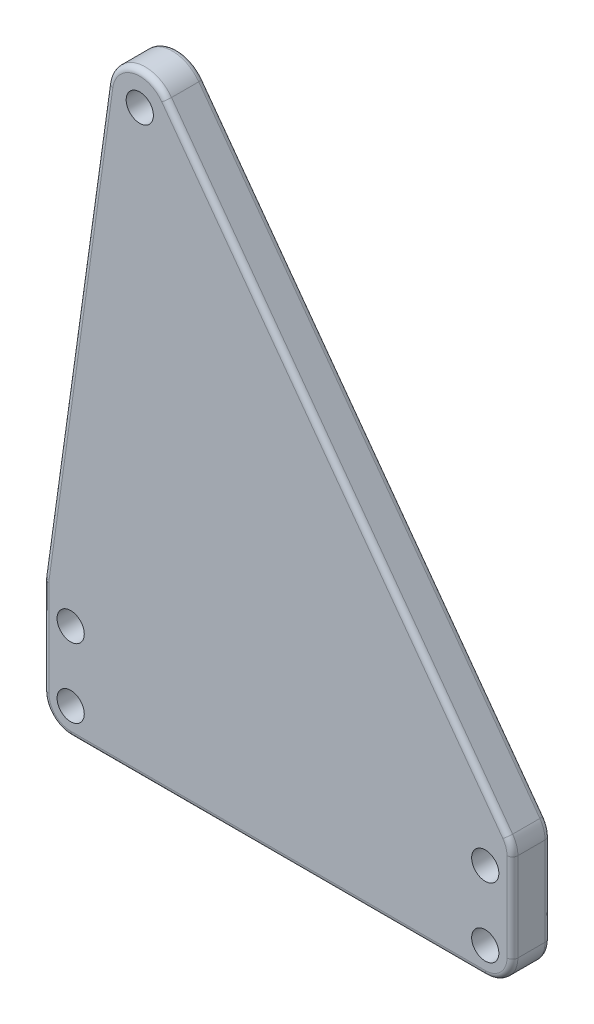
SolidWorks part; units mm, degrees
ref_plane "Front Plane" through (0, 0, 0) normal (0, 0, 1) x (1, 0, 0)
ref_plane "Top Plane" through (0, 0, 0) normal (0, 1, 0) x (1, 0, 0)
ref_plane "Right Plane" through (0, 0, 0) normal (1, 0, 0) x (0, 0, -1)
sketch "Sketch1" plane through (0, 0, 0) normal (0, 0, 1) x (1, 0, 0)
  line L2 (-17.7, -83.6918) -> (-17.7, -106.6)
  line L3 (-17.7, -106.6) -> (68.5, -106.6)
  line L4 (68.5, -83.6918) -> (68.5, -106.6)
  line L6 (-17.7, -83.6918) -> (-5.9428, 0.8267)
  line L7 (68.5, -83.6918) -> (4.8467, 3.5368)
  circle A0 centre (0, 0) radius 2.5
  circle A1 centre (-12.7, -88.9) radius 2.5
  circle A2 centre (-12.7, -101.6) radius 2.5
  circle A3 centre (63.5, -88.9) radius 2.5
  circle A4 centre (63.5, -101.6) radius 2.5
  circle A6 centre (0, 0) radius 6
  dimension "D1" = 5
  dimension "D9" = 12
  dimension "D2" = 101.6
  dimension "D3" = 12.7
  dimension "D4" = 12.7
  dimension "D5" = 76.2
  dimension "D6" = 5
  dimension "D7" = 5
  dimension "D8" = 5
extrude "Boss-Extrude1" add sketch "Sketch1" along normal blind 7 contours A6 L6 L2 L3 L4 L7 A4 A3 A2 A1 | A6 A0
fillet "Fillet1" radius 5 4 edges at (68.5, -106.6, 3.5) (-17.7, -106.6, 3.5) (-17.7, -83.6918, 3.5) (68.5, -83.6918, 3.5)
fillet "Fillet2" radius 1 20 edges at (-17.6881, -83.6926, 0) (-17.7, -92.8189, 0) (-16.2355, -105.1355, 0) (25.4, -106.6, 0) (67.0355, -105.1355, 0) (68.5, -93.4611, 0) (68.2537, -83.7721, 0) (36.1929, -39.419, 0) (-1.4617, 5.8192, 0) (-17.6881, -83.6926, 7) (-17.7, -92.8189, 7) (-16.2355, -105.1355, 7) (25.4, -106.6, 7) (67.0355, -105.1355, 7) (68.5, -93.4611, 7) (68.2537, -83.7721, 7) (36.1929, -39.419, 7) (-1.4617, 5.8192, 7) (-11.7975, -41.2611, 0) (-11.7975, -41.2611, 7)
